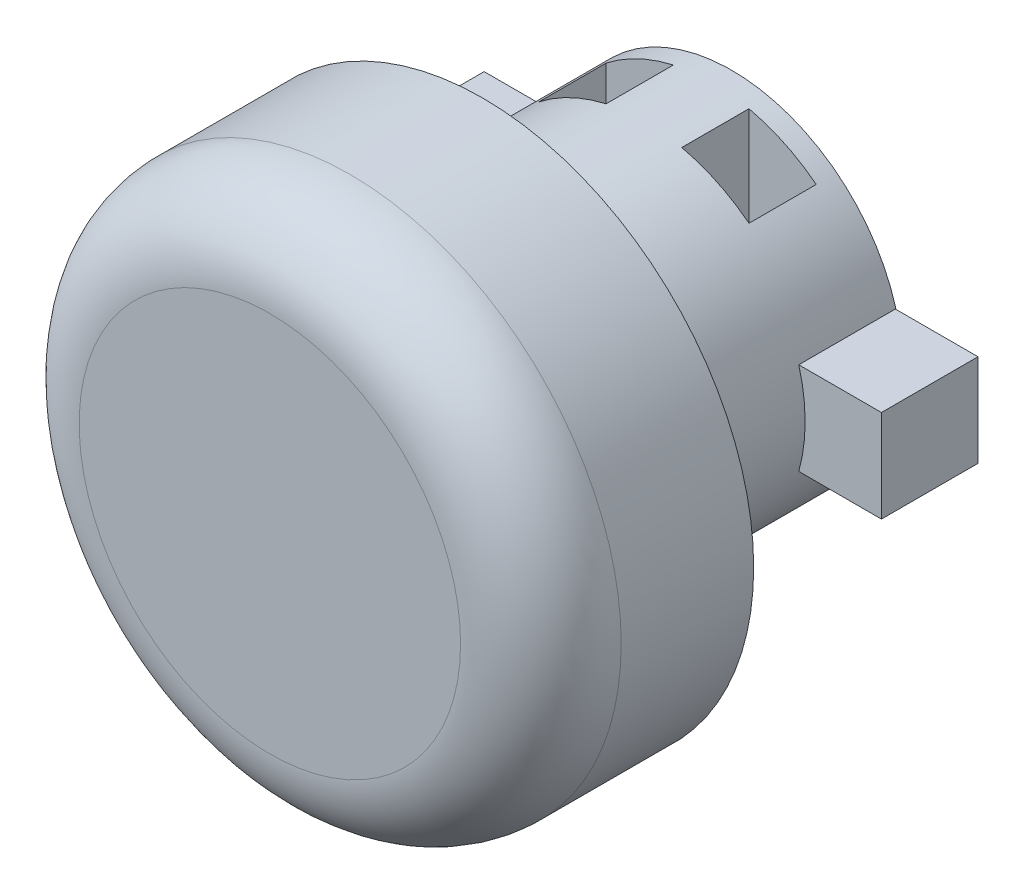
SolidWorks part; units mm, degrees
ref_plane "Front Plane" through (0, 0, 0) normal (0, 0, 1) x (1, 0, 0)
ref_plane "Top Plane" through (0, 0, 0) normal (0, 1, 0) x (1, 0, 0)
ref_plane "Right Plane" through (0, 0, 0) normal (1, 0, 0) x (0, 0, -1)
sketch "Sketch1" plane through (0, 0, 0) normal (0, 0, 1) x (1, 0, 0)
  circle A0 centre (0, 0) radius 42.5
extrude "Boss-Extrude1" add sketch "Sketch1" along normal blind 76
sketch "Sketch2" plane through (0, 0, 76) normal (0, 0, 1) x (1, 0, 0)
  circle A0 centre (0, 0) radius 67.5
extrude "Boss-Extrude2" add sketch "Sketch2" along normal blind 39
fillet "Fillet1" radius 20 1 edges at (67.5, 0, 115)
sketch "Sketch3" plane through (0, 0, 76) normal (0, 0, -1) x (-1, 0, 0)
  circle A0 centre (0, 0) radius 67.5
  circle A2 centre (0, 0) radius 62.5
extrude "Boss-Extrude3" add sketch "Sketch3" along normal blind 14
sketch "Sketch4" plane through (0, 0, 0) normal (0, 1, 0) x (1, 0, 0)
  line L1 (-61.5, -24.18) -> (61.5, -24.18)
  line L2 (-61.5, -24.18) -> (-61.5, -0.1309)
  line L3 (-61.5, -0.1309) -> (61.5, -0.1309)
  line L4 (61.5, -24.18) -> (61.5, -0.1309)
  line L5 (-61.5, -24.18) -> (61.5, -0.1309) construction
  line L6 (-61.5, -0.1309) -> (61.5, -24.18) construction
  point P0 (0, -12.1555)
  point P5 (0, -12.1555)
extrude "Boss-Extrude4" add sketch "Sketch4" along normal mid plane 23
sketch "Sketch5" plane through (0, 0, 0) normal (0, 1, 0) x (1, 0, 0)
  line L0 (0, 0) -> (0, -26.9431) construction
  line L1 (-26.1729, -5.0888) -> (-9.4222, -5.0888)
  line L2 (-26.1729, -5.0888) -> (-26.1729, -21.8394)
  line L3 (-26.1729, -21.8394) -> (-9.4222, -21.8394)
  line L4 (-9.4222, -5.0888) -> (-9.4222, -21.8394)
  line L5 (-26.1729, -5.0888) -> (-9.4222, -21.8394) construction
  line L6 (-26.1729, -21.8394) -> (-9.4222, -5.0888) construction
  line L7 (26.1729, -21.8394) -> (9.4222, -5.0888) construction
  line L8 (26.1729, -5.0888) -> (9.4222, -21.8394) construction
  line L9 (9.4222, -5.0888) -> (9.4222, -21.8394)
  line L10 (26.1729, -21.8394) -> (9.4222, -21.8394)
  line L11 (26.1729, -5.0888) -> (26.1729, -21.8394)
  line L12 (26.1729, -5.0888) -> (9.4222, -5.0888)
  point P0 (-17.7976, -13.4641)
  point P12 (17.7976, -13.4641)
  point P13 (-17.7976, -13.4641)
extrude "Cut-Extrude1" cut sketch "Sketch5" against normal through all both and the other way through all
